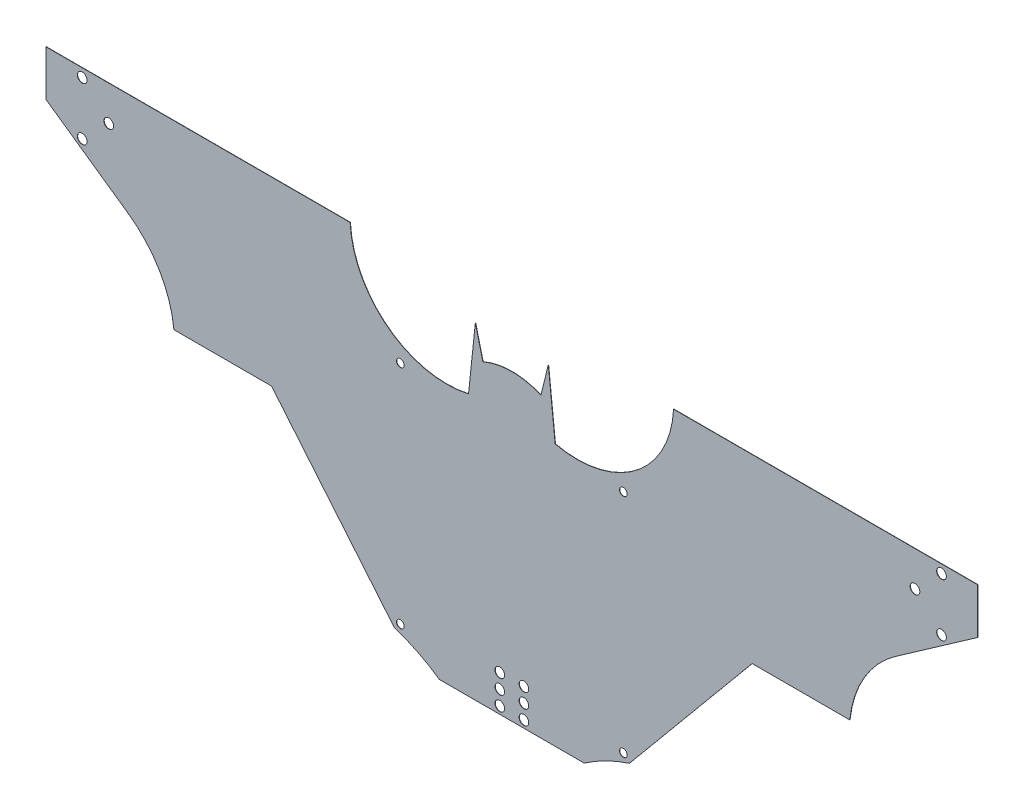
SolidWorks part; units mm, degrees
ref_plane "Front Plane" through (0, 0, 0) normal (0, 0, 1) x (1, 0, 0)
ref_plane "Top Plane" through (0, 0, 0) normal (0, 1, 0) x (1, 0, 0)
ref_plane "Right Plane" through (0, 0, 0) normal (1, 0, 0) x (0, 0, -1)
sketch "Sketch1" plane through (0, 0, 0) normal (0, 0, 1) x (1, 0, 0)
  line L0 (0, 145.9429) -> (0, -145.9429) construction
  line L1 (67, 50) -> (220, 50)
  line L2 (-67, 50) -> (-220, 50)
  line L3 (17.9555, 13) -> (15.1177, 40)
  line L4 (15.1177, 40) -> (12, 27.4955)
  line L5 (-15.1177, 40) -> (-12, 27.4955)
  line L6 (-17.9555, 13) -> (-15.1177, 40)
  line L7 (220, 50) -> (158.9525, 7.2541)
  line L8 (-220, 50) -> (-158.9525, 7.2541)
  line L9 (-140, -25) -> (-99.5632, -25)
  line L10 (140, -25) -> (99.5632, -25)
  arc A0 (67, 50) -> (17.9555, 13) centre (27.0477, 51.953) cw
  arc A1 (-67, 50) -> (-17.9555, 13) centre (-27.0477, 51.953) ccw
  arc A2 (12, 27.4955) -> (-12, 27.4955) centre (0, 0) ccw
  arc A3 (158.9525, 7.2541) -> (140, -25) centre (184.7635, -29.6077) ccw
  arc A4 (-99.5632, -25) -> (0, -115.6638) centre (-99.5632, -125) cw
  arc A5 (99.5632, -25) -> (0, -115.6638) centre (99.5632, -125) ccw
  arc A6 (-158.9525, 7.2541) -> (-140, -25) centre (-184.7635, -29.6077) cw
  dimension "D2" = 40
  dimension "D5" = 30
  dimension "D10" = 220
  dimension "D12" = 45
  dimension "D13" = 100
  dimension "D1" = 134
  dimension "D3" = 84
  dimension "D4" = 160
  dimension "D6" = 50
  dimension "D7" = 24
  dimension "D8" = 37
  dimension "D9" = 10
  dimension "D11" = 35
  dimension "D14" = 140
  dimension "D15" = 75
  dimension "D16" = 140
  dimension "D17" = 99.5632
sketch "Sketch2" plane through (0, 0, 0) normal (0, 0, 1) x (1, 0, 0)
  line L0 (0, 145.9429) -> (0, -145.9429) construction
  line L7 (0, 0) -> (0, -152.8683) construction
  line L8 (99.5632, -21.9265) -> (48.69, -83.15)
  line L9 (-99.5632, -21.9265) -> (-48.69, -83.15)
  line L26 (158.9525, 10.3276) -> (220, 53.0735)
  line L27 (220, 53.0735) -> (67, 53.0735)
  line L28 (17.9555, 16.0735) -> (15.1177, 43.0735)
  line L29 (15.1177, 43.0735) -> (12, 30.569)
  line L30 (-12, 30.569) -> (-15.1177, 43.0735)
  line L31 (-15.1177, 43.0735) -> (-17.9555, 16.0735)
  line L32 (-67, 53.0735) -> (-220, 53.0735)
  line L33 (-220, 53.0735) -> (-158.9525, 10.3276)
  line L34 (-140, -21.9265) -> (-99.5632, -21.9265)
  line L35 (99.5632, -21.9265) -> (140, -21.9265)
  circle A2 centre (46.19, 13) radius 1.5875
  circle A3 centre (-46.19, 13) radius 1.5875
  circle A4 centre (46.19, -80.65) radius 1.5875
  circle A5 centre (-46.19, -80.65) radius 1.5875
  arc A6 (48.69, -83.15) -> (0, -150) centre (70.2366, -150) ccw
  arc A7 (-48.69, -83.15) -> (0, -150) centre (-70.2366, -150) cw
  arc A14 (17.9555, 16.0735) -> (67, 53.0735) centre (27.0477, 55.0265) ccw
  arc A15 (12, 30.569) -> (-12, 30.569) centre (0, 3.0735) ccw
  arc A16 (-67, 53.0735) -> (-17.9555, 16.0735) centre (-27.0477, 55.0265) ccw
  arc A17 (-140, -21.9265) -> (-158.9525, 10.3276) centre (-184.7635, -26.5342) ccw
  arc A20 (158.9525, 10.3276) -> (140, -21.9265) centre (184.7635, -26.5342) ccw
  point P0 (0, 40)
  dimension "D3" = 93.65
  dimension "D4" = 3.175
  dimension "D5" = 3.175
  dimension "D6" = 3.175
  dimension "D7" = 3.175
  dimension "D2" = 40
  dimension "D9" = 25
  dimension "D10" = 46.19
  dimension "D11" = 27
  dimension "D12" = 46.19
  dimension "D13" = 99.5632
  dimension "D14" = 2.5
  dimension "D15" = 2.5
  dimension "D16" = 150
extrude "Boss-Extrude1" add sketch "Sketch2" along normal blind 0.118
sketch "Sketch3" plane through (0, 0, 0) normal (0, 0, -1) x (-1, 0, 0)
  line L0 (0, -121.719) -> (0, 0) construction
  line L1 (178, 49.5735) -> (178, 27.5735) construction
  line L2 (178, 27.5735) -> (178, 49.5735) construction
  line L3 (67, 53.0735) -> (220, 53.0735) construction
  circle A0 centre (178, 49.5735) radius 2
  circle A1 centre (178, 27.5735) radius 2
  circle A2 centre (167, 38.5735) radius 2
  dimension "D1" = 4
  dimension "D2" = 4
  dimension "D5" = 4
  dimension "D3" = 22
  dimension "D4" = 42
  dimension "D6" = 11
  dimension "D7" = 11
  dimension "D8" = 3.5
extrude "Cut-Extrude1" cut sketch "Sketch3" against normal through all
mirror "Mirror2" about plane through (0, 0, 0) normal (1, 0, 0) of "Cut-Extrude1"
chamfer "Chamfer1" distance 27 angle 90 2 edges at (-220, 53.0735, 0.059) (220, 53.0735, 0.059)
sketch "Sketch4" plane through (0, 0, 0) normal (0, 0, -1) x (-1, 0, 0)
  line L5 (-30, -207.569) -> (30, -207.569)
  line L6 (-30, -207.569) -> (-30, -92.431)
  line L7 (-30, -92.431) -> (30, -92.431)
  line L8 (30, -207.569) -> (30, -92.431)
  line L9 (-30, -207.569) -> (30, -92.431) construction
  line L10 (-30, -92.431) -> (30, -207.569) construction
  arc A0 (48.69, -83.15) -> (0, -150) centre (70.2366, -150) ccw construction
  point P0 (0, -150)
  dimension "D1" = 60
extrude "Cut-Extrude2" cut sketch "Sketch4" against normal through all
sketch "Sketch5" plane through (0, 0, 0) normal (0, 0, -1) x (-1, 0, 0)
  line L0 (0, 0) -> (0, -92.431) construction
  line L1 (30, -92.431) -> (-30, -92.431) construction
  circle A0 centre (-5, -89.431) radius 2
  circle A1 centre (5, -89.431) radius 2
  dimension "D1" = 4
  dimension "D2" = 5
  dimension "D3" = 3
  dimension "D4" = 2
extrude "Cut-Extrude3" cut sketch "Sketch5" against normal through all contours A0 | A1
pattern_linear "LPattern1" count 3 spacing 6 along (0, 1, 0) of "Cut-Extrude3"
